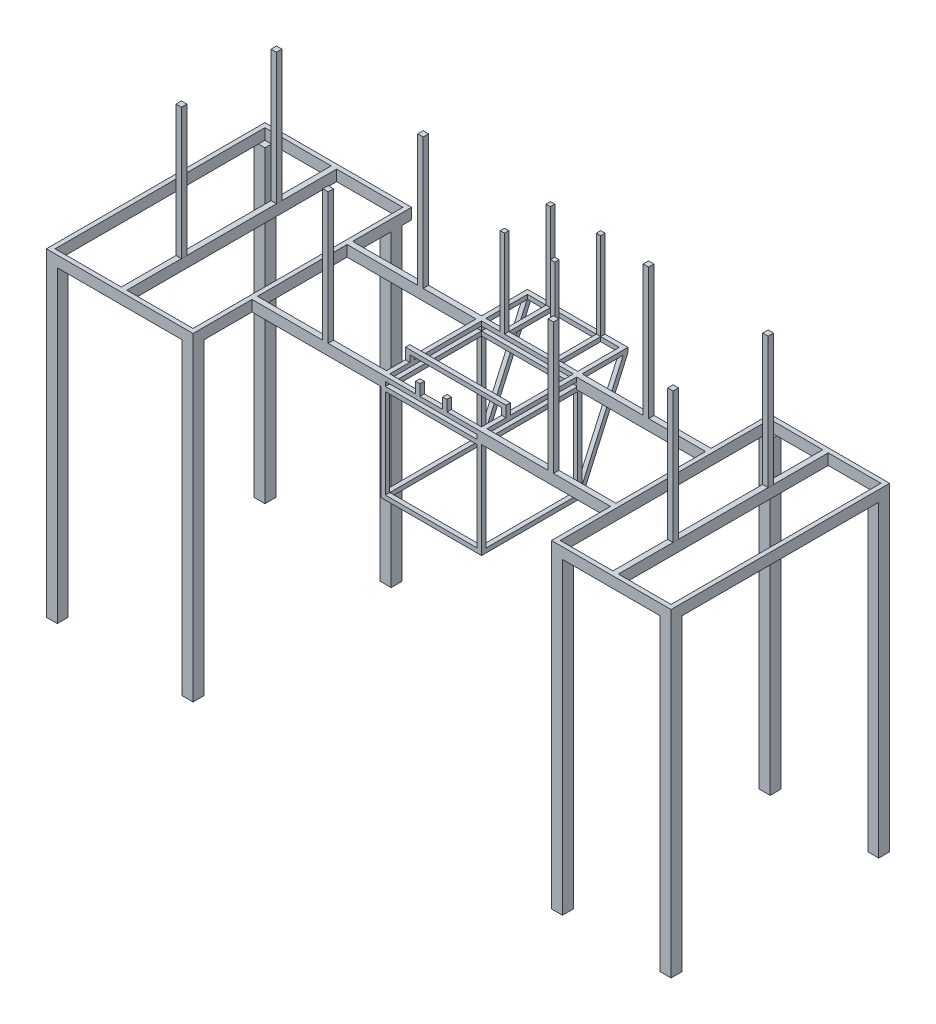
SolidWorks part; units mm, degrees
ref_plane "Front" through (0, 0, 0) normal (0, 0, 1) x (1, 0, 0)
ref_plane "Top" through (0, 0, 0) normal (0, 1, 0) x (1, 0, 0)
ref_plane "Right" through (0, 0, 0) normal (1, 0, 0) x (0, 0, -1)
sketch "Croquis1" plane through (0, 0, 0) normal (0, 1, 0) x (1, 0, 0)
  line L0 (20, 20) -> (440, 20)
  line L1 (0, 0) -> (460, 0)
  line L2 (0, 0) -> (0, 460)
  line L3 (0, 460) -> (460, 460)
  line L4 (460, 0) -> (460, 460)
  line L5 (440, 20) -> (440, 440)
  line L6 (20, 440) -> (440, 440)
  line L7 (20, 20) -> (20, 440)
  dimension "D1" = 20
  dimension "D2" = 420
extrude "Saliente-Extruir1" add sketch "Croquis1" along normal blind 20
sketch "Croquis2" plane through (0, 0, 0) normal (0, -1, 0) x (1, 0, 0)
  line L1 (0, 0) -> (20, 0)
  line L2 (0, 0) -> (0, -20)
  line L3 (0, -20) -> (20, -20)
  line L4 (20, 0) -> (20, -20)
  line L5 (0, -460) -> (20, -460)
  line L6 (0, -460) -> (0, -440)
  line L7 (0, -440) -> (20, -440)
  line L8 (20, -460) -> (20, -440)
  line L9 (460, -460) -> (440, -460)
  line L10 (460, -460) -> (460, -440)
  line L11 (460, -440) -> (440, -440)
  line L12 (440, -460) -> (440, -440)
  line L13 (460, 0) -> (440, 0)
  line L14 (460, 0) -> (460, -20)
  line L15 (460, -20) -> (440, -20)
  line L16 (440, 0) -> (440, -20)
extrude "Saliente-Extruir2" add sketch "Croquis2" along normal blind 20
sketch "Croquis3" plane through (0, -20, 0) normal (0, -1, 0) x (1, 0, 0)
  line L0 (20, -440) -> (20, -20)
  line L1 (0, -460) -> (460, -460)
  line L2 (0, -460) -> (0, 0)
  line L3 (0, 0) -> (460, 0)
  line L4 (460, -460) -> (460, 0)
  line L5 (20, -20) -> (440, -20)
  line L6 (440, -440) -> (440, -20)
  line L7 (20, -440) -> (440, -440)
  dimension "D1" = 20
extrude "Saliente-Extruir3" add sketch "Croquis3" along normal blind 20
sketch "Croquis4" plane through (0, -40, 0) normal (0, -1, 0) x (1, 0, 0)
  line L0 (460, -460) -> (460, 0) construction
  line L1 (0, 0) -> (20, 0)
  line L2 (0, 0) -> (0, -20)
  line L3 (0, -20) -> (20, -20)
  line L4 (20, 0) -> (20, -20)
  line L5 (0, -460) -> (20, -460)
  line L6 (0, -460) -> (0, -440)
  line L7 (0, -440) -> (20, -440)
  line L8 (20, -460) -> (20, -440)
  line L9 (460, -460) -> (440, -460)
  line L10 (460, -460) -> (460, -440)
  line L11 (460, -440) -> (440, -440)
  line L12 (440, -460) -> (440, -440)
  line L13 (460, 0) -> (440, 0)
  line L14 (460, 0) -> (460, -20)
  line L15 (460, -20) -> (440, -20)
  line L16 (440, 0) -> (440, -20)
  line L17 (460, 0) -> (0, 0) construction
extrude "Saliente-Extruir4" add sketch "Croquis4" along normal blind 410
sketch "Croquis5" plane through (0, -450, 0) normal (0, -1, 0) x (1, 0, 0)
  line L0 (20, -440) -> (20, -20)
  line L1 (0, -460) -> (460, -460)
  line L2 (0, -460) -> (0, 0)
  line L3 (0, 0) -> (460, 0)
  line L4 (460, -460) -> (460, 0)
  line L5 (20, -20) -> (440, -20)
  line L6 (440, -440) -> (440, -20)
  line L7 (20, -440) -> (440, -440)
  dimension "D1" = 20
extrude "Saliente-Extruir5" add sketch "Croquis5" along normal blind 20
sketch "Croquis6" plane through (0, -470, 0) normal (0, -1, 0) x (1, 0, 0)
  line L1 (440, -20) -> (20, -20) construction
  line L2 (0, -460) -> (20, -460)
  line L3 (0, -460) -> (0, -440)
  line L4 (0, -440) -> (20, -440)
  line L5 (20, -460) -> (20, -440)
  line L6 (460, -460) -> (440, -460)
  line L7 (460, -460) -> (460, -440)
  line L8 (460, -440) -> (440, -440)
  line L9 (440, -460) -> (440, -440)
  line L10 (460, 0) -> (440, 0)
  line L11 (460, 0) -> (460, -20)
  line L12 (460, -20) -> (440, -20)
  line L13 (440, 0) -> (440, -20)
  line L14 (440, -440) -> (440, -20) construction
  line L16 (0, 0) -> (20, 0)
  line L17 (0, 0) -> (0, -20)
  line L18 (0, -20) -> (20, -20)
  line L19 (20, 0) -> (20, -20)
sketch "Croquis7" plane through (0, 0, 0) normal (-1, 0, 0) x (0, 0, 1)
  line L1 (0, 20) -> (-25, 20)
  line L2 (0, 20) -> (0, -30)
  line L3 (0, -30) -> (-25, -30)
  line L4 (-25, 20) -> (-25, -30)
  line L5 (-230, 0) -> (-230, -450) construction
  line L6 (-440, 0) -> (-20, 0) construction
  line L7 (-20, -450) -> (-440, -450) construction
  line L8 (-435, 20) -> (-435, -30)
  line L9 (-460, -30) -> (-435, -30)
  line L10 (-460, 20) -> (-460, -30)
  line L11 (-460, 20) -> (-435, 20)
  dimension "D1" = 50
  dimension "D2" = 25
extrude "Saliente-Extruir7" add sketch "Croquis7" along normal blind 590
sketch "Croquis8" plane through (460, 0, 0) normal (1, 0, 0) x (0, 0, -1)
  line L0 (230, 20) -> (230, -450) construction
  line L1 (0, 20) -> (25, 20)
  line L2 (0, 20) -> (0, -30)
  line L3 (0, -30) -> (25, -30)
  line L4 (25, 20) -> (25, -30)
  line L5 (0, 20) -> (460, 20) construction
  line L6 (440, -450) -> (20, -450) construction
  line L7 (435, 20) -> (435, -30)
  line L8 (460, -30) -> (435, -30)
  line L9 (460, 20) -> (460, -30)
  line L10 (460, 20) -> (435, 20)
  dimension "D1" = 25
  dimension "D2" = 50
extrude "Saliente-Extruir8" add sketch "Croquis8" along normal blind 590
sketch "Croquis9" plane through (0, 20, 0) normal (0, 1, 0) x (1, 0, 0)
  line L0 (1050, 460) -> (-590, 460) construction
  line L1 (-267, 460) -> (-242, 460)
  line L2 (-267, 460) -> (-267, 435)
  line L3 (-267, 435) -> (-242, 435)
  line L4 (-242, 460) -> (-242, 435)
  line L5 (-590, 435) -> (0, 435) construction
  line L6 (0, 230) -> (-607.3919, 230) construction
  line L7 (0, 435) -> (0, 25) construction
  line L8 (-242, 0) -> (-242, 25)
  line L9 (-267, 25) -> (-242, 25)
  line L10 (-267, 0) -> (-267, 25)
  line L11 (-267, 0) -> (-242, 0)
  line L12 (1050, 435) -> (460, 435) construction
  line L13 (764, 460) -> (789, 460)
  line L14 (764, 460) -> (764, 435)
  line L15 (764, 435) -> (789, 435)
  line L16 (789, 460) -> (789, 435)
  line L17 (1050, 25) -> (460, 25) construction
  line L18 (764, 25) -> (789, 25)
  line L19 (764, 25) -> (764, 0)
  line L20 (764, 0) -> (789, 0)
  line L21 (789, 25) -> (789, 0)
  line L22 (-590, 0) -> (1050, 0) construction
  line L23 (-590, 435) -> (-590, 25) construction
  line L24 (-913, 0) -> (-938, 0)
  line L25 (-913, 0) -> (-913, 25)
  line L26 (-913, 25) -> (-938, 25)
  line L27 (-938, 0) -> (-938, 25)
  line L28 (-938, 460) -> (-938, 435)
  line L29 (-913, 435) -> (-938, 435)
  line L30 (-913, 460) -> (-913, 435)
  line L31 (-913, 460) -> (-938, 460)
  line L32 (1050, 435) -> (1050, 25) construction
  line L33 (1311, 25) -> (1311, 0)
  line L34 (1336, 0) -> (1311, 0)
  line L35 (1336, 25) -> (1336, 0)
  line L36 (1336, 25) -> (1311, 25)
  line L37 (1311, 460) -> (1311, 435)
  line L38 (1336, 435) -> (1311, 435)
  line L39 (1336, 460) -> (1336, 435)
  line L40 (1336, 460) -> (1311, 460)
  dimension "D1" = 25
  dimension "D2" = 323
  dimension "D3" = 25
  dimension "D4" = 25
  dimension "D5" = 261
extrude "Saliente-Extruir9" add sketch "Croquis9" along normal blind 600
sketch "Croquis10" plane through (0, 20, 0) normal (0, 1, 0) x (1, 0, 0)
  line L0 (-1458.4169, 230) -> (1840.1916, 230) construction
  line L1 (-925.5, 435) -> (-925.5, 25) construction
  line L2 (-938, 435) -> (-913, 435) construction
  line L3 (-913, 25) -> (-938, 25) construction
  line L4 (-610, -250) -> (-913, -250)
  line L5 (-1241, 710) -> (-1241, -250)
  line L6 (1323.5, 435) -> (1323.5, 25) construction
  line L7 (1311, 435) -> (1336, 435) construction
  line L8 (1336, 25) -> (1311, 25) construction
  line L9 (-590, 730) -> (-590, -270)
  line L10 (-590, -270) -> (-1261, -270)
  line L11 (-590, 730) -> (-1261, 730)
  line L12 (-1261, 730) -> (-1261, -270)
  line L13 (-610, 710) -> (-913, 710)
  line L14 (-610, 710) -> (-610, -250)
  line L15 (1070, 710) -> (1070, -250)
  line L16 (1597, 730) -> (1050, 730)
  line L17 (1597, 730) -> (1597, -270)
  line L18 (1597, -270) -> (1050, -270)
  line L19 (1050, 730) -> (1050, -270)
  line L20 (1597, 730) -> (1050, -270) construction
  line L21 (1597, -270) -> (1050, 730) construction
  line L22 (1577, -250) -> (1336, -250)
  line L23 (1577, 710) -> (1577, -250)
  line L24 (1577, 710) -> (1336, 710)
  line L25 (-913, 710) -> (-913, -250)
  line L26 (-938, 710) -> (-938, -250)
  line L27 (1336, -250) -> (1336, 710)
  line L28 (1311, 710) -> (1311, -250)
  line L29 (1311, -250) -> (1070, -250)
  line L30 (1577, -250) -> (1070, -250) construction
  line L31 (1311, 710) -> (1070, 710)
  line L32 (1577, 710) -> (1070, 710) construction
  line L33 (-938, -250) -> (-1241, -250)
  line L34 (-610, -250) -> (-1241, -250) construction
  line L35 (-938, 710) -> (-1241, 710)
  line L36 (-610, 710) -> (-1241, 710) construction
  point P22 (-590, 230)
  point P24 (-925.5, -270)
  point P25 (-925.5, 730)
  point P27 (1323.5, 230)
  dimension "D1" = 500
  dimension "D2" = 230
  dimension "D3" = 20
  dimension "D4" = 1000
  dimension "D5" = 547
  dimension "D6" = 20
extrude "Saliente-Extruir10" add sketch "Croquis10" against normal blind 50
sketch "Croquis11" plane through (0, -30, 0) normal (0, -1, 0) x (1, 0, 0)
  line L0 (-590, -460) -> (-590, -730) construction
  line L1 (-1261, 270) -> (-1211, 270)
  line L2 (-1261, 270) -> (-1261, 220)
  line L3 (-1261, 220) -> (-1211, 220)
  line L4 (-1211, 270) -> (-1211, 220)
  line L5 (-590, 270) -> (-640, 270)
  line L6 (-590, 270) -> (-590, 220)
  line L7 (-590, 220) -> (-640, 220)
  line L8 (-640, 270) -> (-640, 220)
  line L9 (-590, -686.4772) -> (-640, -686.4772)
  line L10 (-590, -686.4772) -> (-590, -636.4772)
  line L11 (-590, -636.4772) -> (-640, -636.4772)
  line L12 (-640, -686.4772) -> (-640, -636.4772)
  line L13 (1597, 270) -> (1597, -730) construction
  line L14 (-1261, -730) -> (-1211, -730)
  line L15 (-1261, -730) -> (-1261, -680)
  line L16 (-1261, -680) -> (-1211, -680)
  line L17 (-1211, -730) -> (-1211, -680)
  line L18 (1050, -730) -> (1100, -730)
  line L19 (1050, -730) -> (1050, -680)
  line L20 (1050, -680) -> (1100, -680)
  line L21 (1100, -730) -> (1100, -680)
  line L22 (1597, -730) -> (1547, -730)
  line L23 (1597, -730) -> (1597, -680)
  line L24 (1597, -680) -> (1547, -680)
  line L25 (1547, -730) -> (1547, -680)
  line L26 (1597, 270) -> (1547, 270)
  line L27 (1597, 270) -> (1597, 220)
  line L28 (1597, 220) -> (1547, 220)
  line L29 (1547, 270) -> (1547, 220)
  line L30 (1050, 270) -> (1100, 270)
  line L31 (1050, 270) -> (1050, 220)
  line L32 (1050, 220) -> (1100, 220)
  line L33 (1100, 270) -> (1100, 220)
  line L34 (1050, 270) -> (1597, 270) construction
  dimension "D2" = 50
  dimension "D1" = 50
  dimension "D3" = 50
  dimension "D4" = 50
  dimension "D5" = 50
  dimension "D6" = 50
  dimension "D7" = 50
  dimension "D8" = 50
  dimension "D9" = 50
  dimension "D10" = 50
  dimension "D11" = 50
  dimension "D12" = 50
  dimension "D13" = 50
  dimension "D14" = 50
  dimension "D15" = 50
  dimension "D16" = 50
extrude "Saliente-Extruir11" add sketch "Croquis11" along normal blind 1410
sketch "Croquis13" plane through (0, 0, -460) normal (0, 0, -1) x (-1, 0, 0)
  line L0 (-230, -450) -> (-230, -20) construction
  line L2 (-20, -450) -> (-440, -450) construction
  line L3 (-20, -20) -> (-440, -20) construction
  line L4 (-764, 20) -> (242, 20) construction
  line L5 (-335, 20) -> (-355, 20)
  line L6 (-335, 20) -> (-335, 0)
  line L7 (-335, 0) -> (-355, 0)
  line L8 (-355, 20) -> (-355, 0)
  line L9 (-440, 0) -> (-20, 0) construction
  line L10 (-105, 20) -> (-105, 0)
  line L11 (-125, 0) -> (-105, 0)
  line L12 (-125, 20) -> (-125, 0)
  line L13 (-125, 20) -> (-105, 20)
  dimension "D1" = 20
  dimension "D2" = 105
extrude "Saliente-Extruir12" add sketch "Croquis13" along normal blind 210
sketch "Croquis14" plane through (125, 0, 0) normal (1, 0, 0) x (0, 0, -1)
  line L0 (670, 0) -> (460, 0) construction
  line L1 (670, 20) -> (650, 20)
  line L2 (670, 20) -> (670, 0)
  line L3 (670, 0) -> (650, 0)
  line L4 (650, 20) -> (650, 0)
  dimension "D1" = 20
extrude "Saliente-Extruir13" add sketch "Croquis14" along normal up to surface (210 mm away) up to face at (335, 10, -565)
sketch "Croquis15" plane through (0, 20, 0) normal (0, 1, 0) x (1, 0, 0)
  line L0 (230, 20) -> (230, 165.9322) construction
  line L1 (20, 20) -> (440, 20) construction
  line L2 (-242, 0) -> (764, 0) construction
  line L3 (302, 0) -> (282, 0)
  line L4 (302, 0) -> (302, 20)
  line L5 (302, 20) -> (282, 20)
  line L6 (282, 0) -> (282, 20)
  line L7 (178, 0) -> (178, 20)
  line L8 (158, 20) -> (178, 20)
  line L9 (158, 0) -> (158, 20)
  line L10 (158, 0) -> (178, 0)
  dimension "D1" = 20
  dimension "D2" = 52
extrude "Saliente-Extruir14" add sketch "Croquis15" along normal blind 50
sketch "Croquis16" plane through (0, 20, 0) normal (0, 1, 0) x (1, 0, 0)
  line L0 (440, 440) -> (20, 440) construction
  line L1 (355, 670) -> (335, 670)
  line L2 (355, 670) -> (355, 650)
  line L3 (355, 650) -> (335, 650)
  line L4 (335, 670) -> (335, 650)
  line L5 (105, 670) -> (125, 670)
  line L6 (105, 670) -> (105, 650)
  line L7 (105, 650) -> (125, 650)
  line L8 (125, 670) -> (125, 650)
  line L9 (335, 460) -> (355, 460)
  line L10 (335, 460) -> (335, 440)
  line L11 (335, 440) -> (355, 440)
  line L12 (355, 460) -> (355, 440)
  line L14 (125, 460) -> (105, 460)
  line L15 (125, 460) -> (125, 440)
  line L16 (125, 440) -> (105, 440)
  line L17 (105, 460) -> (105, 440)
extrude "Saliente-Extruir15" add sketch "Croquis16" along normal blind 400
sketch "Croquis17" plane through (0, 20, 0) normal (0, 1, 0) x (1, 0, 0)
  line L1 (0, 440) -> (460, 440)
  line L2 (0, 440) -> (0, 670)
  line L3 (0, 670) -> (460, 670)
  line L4 (460, 440) -> (460, 670)
  line L5 (20, 460) -> (440, 460)
  line L6 (20, 460) -> (20, 650)
  line L7 (20, 650) -> (440, 650)
  line L8 (440, 460) -> (440, 650)
extrude "Saliente-Extruir16" add sketch "Croquis17" against normal blind 20
sketch "Croquis18" plane through (0, 0, 0) normal (-1, 0, 0) x (0, 0, 1)
  line L0 (-670, 0) -> (-460, -470)
  line L1 (-651.7398, 8.1588) -> (-441.7398, -461.8412)
  line L2 (-460, -470) -> (-441.7398, -461.8412)
  line L3 (-670, 0) -> (-651.7398, 8.1588)
  dimension "D1" = 20
extrude "Saliente-Extruir17" add sketch "Croquis18" against normal blind 20
sketch "Croquis19" plane through (460, 0, 0) normal (1, 0, 0) x (0, 0, -1)
  line L0 (670, 0) -> (460, -470)
  line L1 (651.7398, 8.1588) -> (441.7398, -461.8412)
  line L2 (460, -470) -> (441.7398, -461.8412)
  line L3 (670, 0) -> (651.7398, 8.1588)
  dimension "D1" = 20
extrude "Saliente-Extruir18" add sketch "Croquis19" against normal blind 20
sketch "Croquis23" plane through (0, 20, 0) normal (0, 1, 0) x (1, 0, 0)
  line L0 (0, 435) -> (0, 25) construction
  line L1 (0, 112) -> (20, 112)
  line L2 (0, 112) -> (0, 132)
  line L3 (0, 132) -> (20, 132)
  line L4 (20, 112) -> (20, 132)
  line L5 (20, 440) -> (20, 20) construction
  line L6 (440, 20) -> (440, 440) construction
  line L7 (440, 112) -> (460, 112)
  line L8 (440, 112) -> (440, 132)
  line L9 (440, 132) -> (460, 132)
  line L10 (460, 112) -> (460, 132)
  line L11 (460, 25) -> (460, 435) construction
  line L13 (302, 0) -> (764, 0) construction
  line L14 (-242, 0) -> (158, 0) construction
  dimension "D1" = 20
  dimension "D2" = 20
  dimension "D3" = 20
  dimension "D4" = 132
  dimension "D5" = 132
extrude "Saliente-Extruir22" add sketch "Croquis23" along normal blind 50
sketch "Croquis24" plane through (440, 0, 0) normal (-1, 0, 0) x (0, 0, 1)
  line L0 (-112, 70) -> (-112, 20) construction
  line L1 (-132, 70) -> (-112, 70)
  line L2 (-132, 70) -> (-132, 50)
  line L3 (-132, 50) -> (-112, 50)
  line L4 (-112, 70) -> (-112, 50)
  dimension "D1" = 20
extrude "Saliente-Extruir23" add sketch "Croquis24" along normal up to surface (420 mm away) up to face at (20, 27.5, -176)
equation "\"Alto\"= 50mm"
equation "\"Ancho\"= \"Alto\" / 2"
equation "\"D2@Croquis8\"=\"Alto\""
equation "\"D1@Croquis9\"=\"Ancho\""
equation "\"D3@Croquis9\"=\"Ancho\""
equation "\"D4@Croquis9\"=\"Ancho\""
equation "\"D9@Croquis11\"=\"Alto\""
equation "\"D10@Croquis11\"=\"Alto\""
equation "\"D11@Croquis11\"=\"Alto\""
